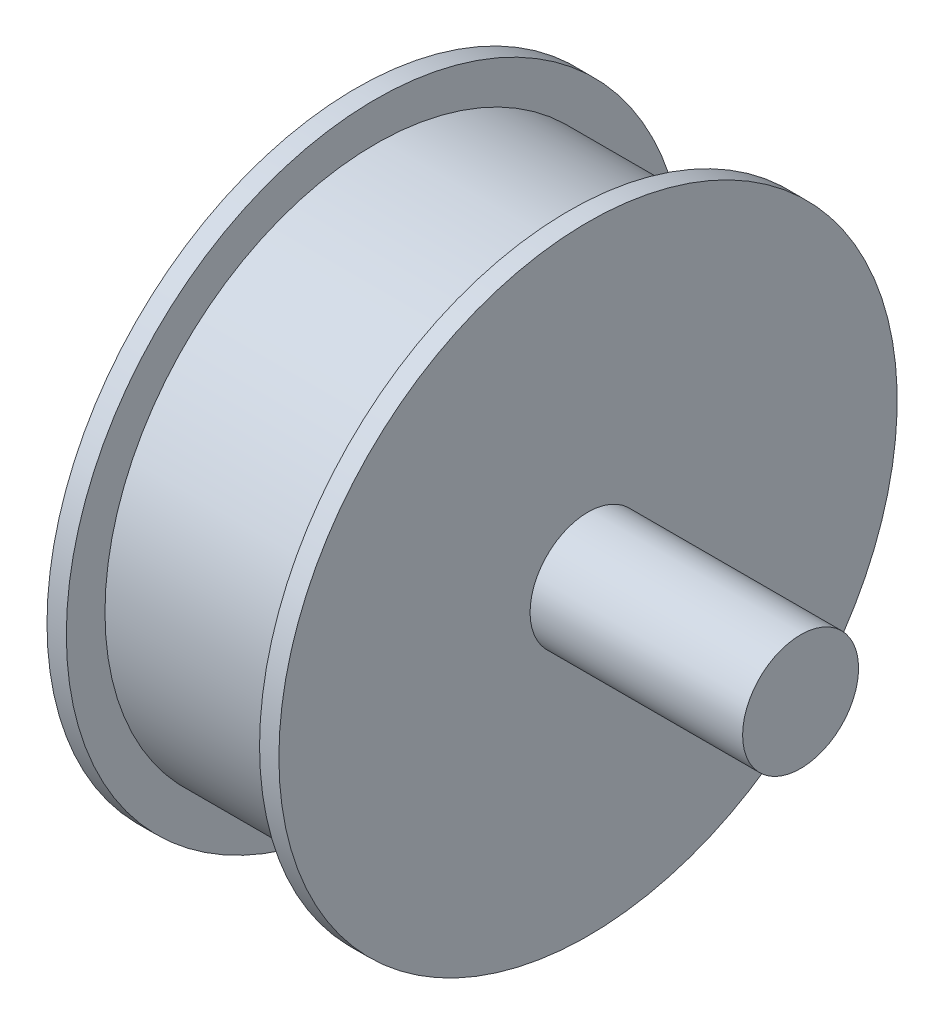
SolidWorks part; units mm, degrees
material "Plain Carbon Steel"
ref_plane "Front Plane" through (0, 0, 0) normal (0, 0, 1) x (1, 0, 0)
ref_plane "Top Plane" through (0, 0, 0) normal (0, 1, 0) x (1, 0, 0)
ref_plane "Right Plane" through (0, 0, 0) normal (1, 0, 0) x (0, 0, -1)
sketch "Sketch1" plane through (0, 0, 0) normal (0, 0, 1) x (1, 0, 0)
  line L0 (0, 7.5) -> (0, 40)
  line L1 (0, 40) -> (-2.5, 40)
  line L2 (-2.5, 40) -> (-2.5, 35)
  line L3 (-2.5, 35) -> (-27.5, 35)
  line L4 (-27.5, 35) -> (-27.5, 40)
  line L5 (-27.5, 40) -> (-30, 40)
  line L6 (-30, 40) -> (-30, 30)
  line L7 (-27.5, 0) -> (27.5, 0)
  line L8 (27.5, 0) -> (27.5, 7.5)
  line L9 (27.5, 7.5) -> (0, 7.5)
  line L10 (-27.5, 0) -> (-27.5, 5)
  line L11 (-30, 5) -> (-27.5, 5)
  line L13 (-30, 10) -> (-25, 10)
  line L14 (-25, 10) -> (-25, 30)
  line L15 (-25, 30) -> (-30, 30)
  line L16 (-30, 10) -> (-30, 5)
  dimension "D1" = 27.5
  dimension "D2" = 35
  dimension "D4" = 2.5
  dimension "D5" = 25
  dimension "D6" = 27.5
  dimension "D7" = 7.5
  dimension "D3" = 2.5
  dimension "D8" = 5
  dimension "D9" = 40
  dimension "D10" = 20
  dimension "D11" = 5
  dimension "D12" = 5
revolve "Revolve1" add sketch "Sketch1" angle 360 about L7
fillet "Fillet1" radius 1 1 edges at (-30, 0, 10)
equation "\"D6@Sketch1\"=\"D1@Sketch1\""
